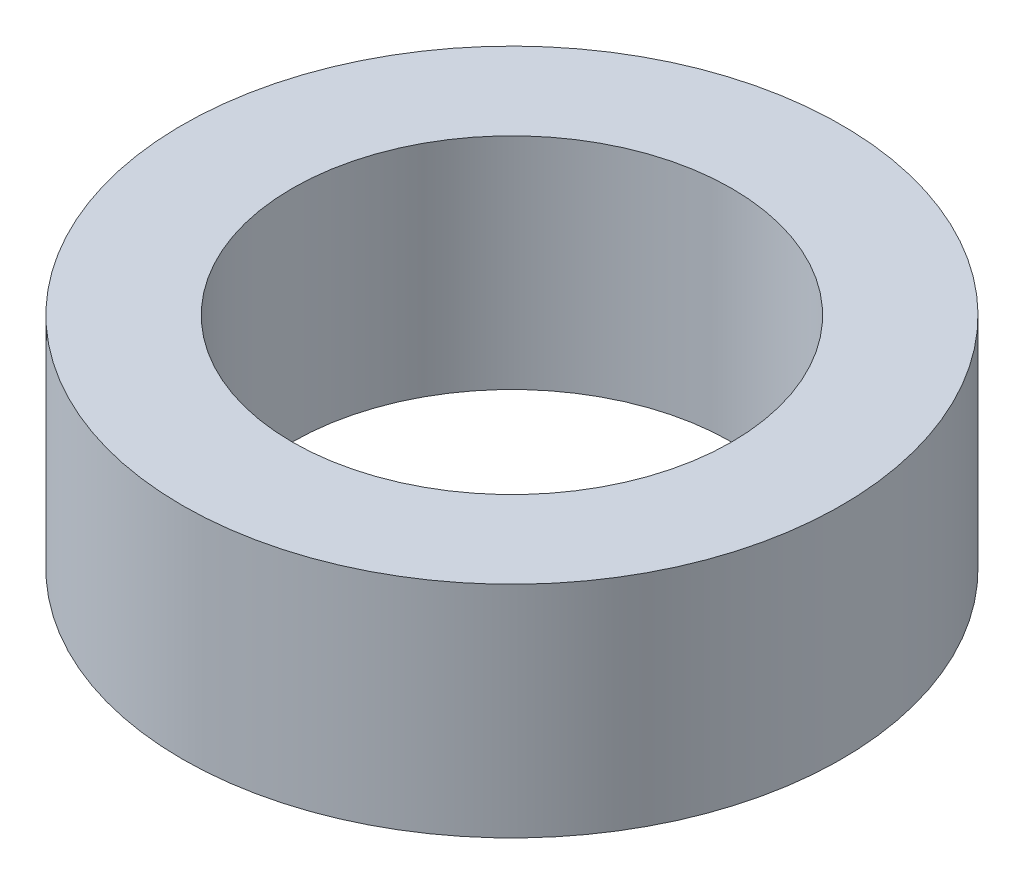
SolidWorks part; units mm, degrees
ref_plane "前视基准面" through (0, 0, 0) normal (0, 0, 1) x (1, 0, 0)
ref_plane "上视基准面" through (0, 0, 0) normal (0, 1, 0) x (1, 0, 0)
ref_plane "右视基准面" through (0, 0, 0) normal (1, 0, 0) x (0, 0, -1)
other "Configuration Table"
sketch "草图1" plane through (0, 0, 0) normal (0, 1, 0) x (1, 0, 0)
  circle A0 centre (0, 0) radius 5
  circle A1 centre (0, 0) radius 7.5
  dimension "D1" = 10
  dimension "D2" = 15
extrude "凸台-拉伸1" add sketch "草图1" along normal blind 5
